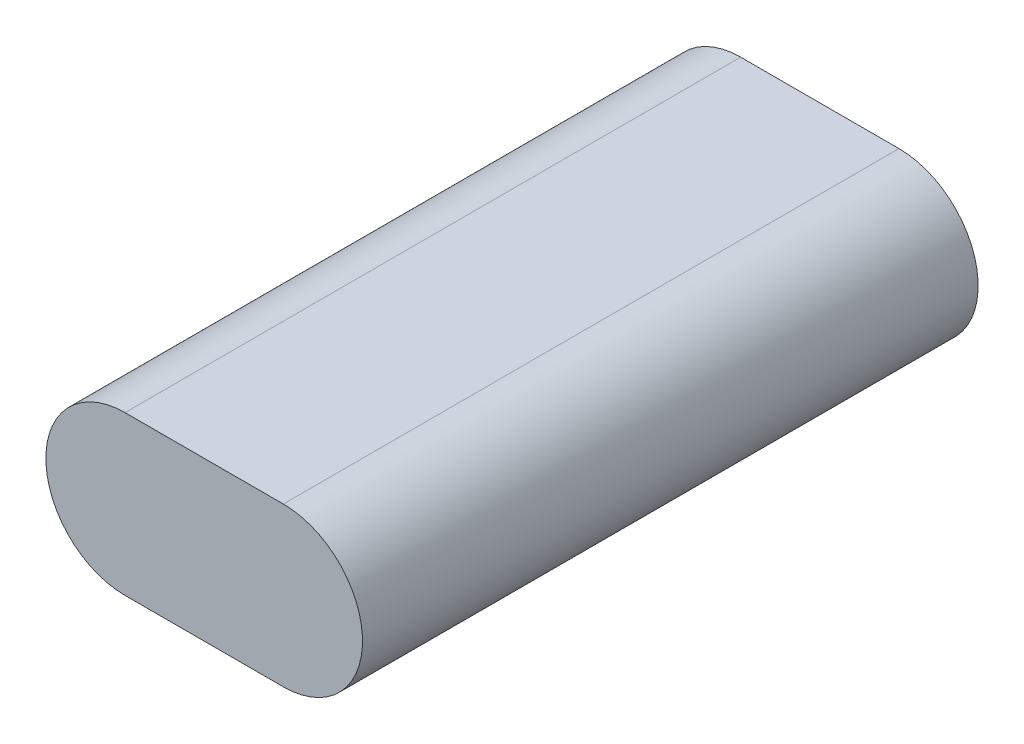
SolidWorks part; units mm, degrees
ref_plane "Front Plane" through (0, 0, 0) normal (0, 0, 1) x (1, 0, 0)
ref_plane "Top Plane" through (0, 0, 0) normal (0, 1, 0) x (1, 0, 0)
ref_plane "Right Plane" through (0, 0, 0) normal (1, 0, 0) x (0, 0, -1)
sketch "Sketch1" plane through (0, 0, 0) normal (0, 0, 1) x (1, 0, 0)
  line L0 (-9, 9) -> (9, 9)
  line L1 (-9, -9) -> (9, -9)
  arc A0 (-9, 9) -> (-9, -9) centre (-9, 0) ccw
  arc A1 (9, -9) -> (9, 9) centre (9, 0) ccw
  arc A2 (0, 0) -> (-9, 9) centre (-9, 0) ccw construction
  arc A3 (9, 9) -> (0, 0) centre (9, 0) ccw construction
  arc A4 (-9, -9) -> (0, 0) centre (-9, 0) ccw construction
  arc A5 (0, 0) -> (9, -9) centre (9, 0) ccw construction
  dimension "D1" = 18
extrude "Boss-Extrude1" add sketch "Sketch1" along normal blind 70 contours L0 A1 L1 A0
